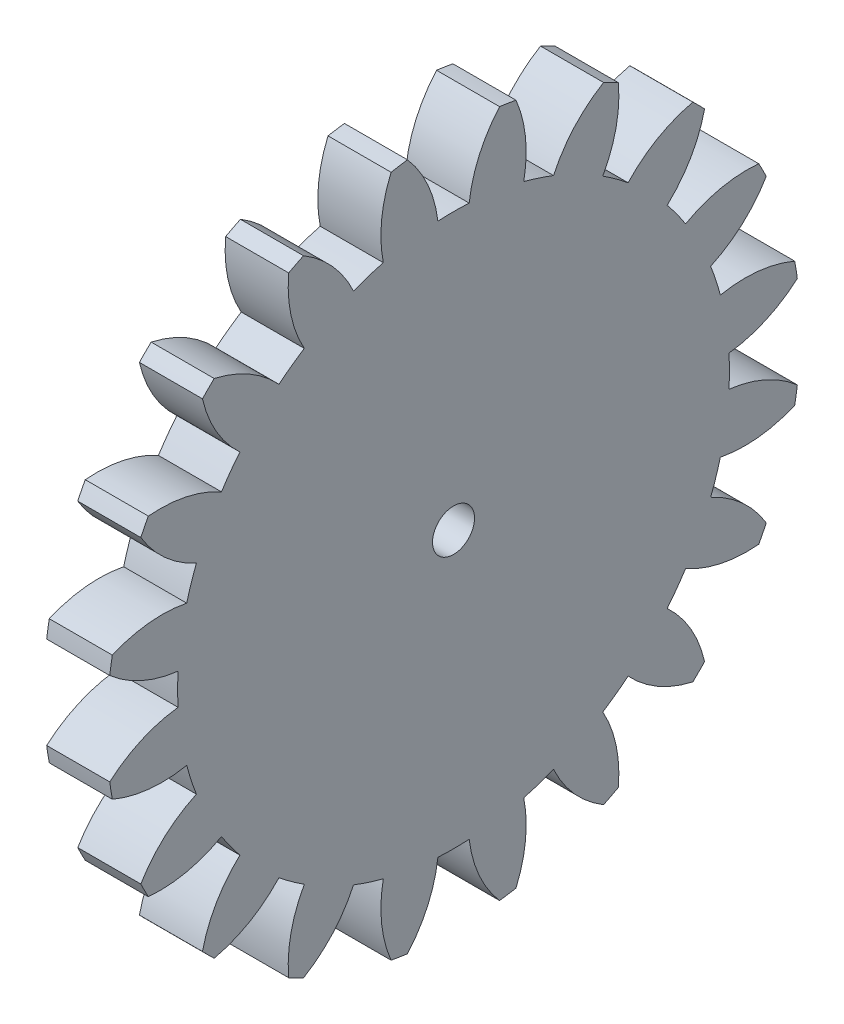
SolidWorks part; units mm, degrees
ref_plane "Plane1" through (0, 0, 0) normal (0, 0, 1) x (1, 0, 0)
ref_plane "Plane2" through (0, 0, 0) normal (0, 1, 0) x (1, 0, 0)
ref_plane "Plane3" through (0, 0, 0) normal (1, 0, 0) x (0, 0, -1)
other "Configuration Table"
sketch "HoldingSke" plane through (0, 0, 0) normal (0, 1, 0) x (1, 0, 0)
  line L0 (0, 0) -> (0.3132, -0.114)
  line L1 (-15, 0) -> (100, 0) construction
  line L2 (0, 0) -> (-2.1039, 2.3779)
  line L3 (0, 0) -> (-11.863, 4.5341)
  line L4 (0, 0) -> (8.1152, 2.9537)
  line L5 (0, 0) -> (-46.8476, -17.4728)
  line L6 (0, 0) -> (-4.9738, -3.3558)
  line L7 (-2.1039, 2.3779) -> (8.6586, 51.2059)
  line L8 (-76.2, 54.61) -> (-75.5, 54.61)
  line L9 (-71.009, 38.7566) -> (-53.1078, 45.2721)
  line L10 (-76.2, 71.12) -> (104.1128, 71.12)
  line L11 (0, 0) -> (-6, 0)
  line L12 (-76.2, 101.6) -> (-76.093, 101.6)
  line L13 (24.9733, 27.94) -> (52.9518, 28.4284)
  line L14 (24.9733, 27.94) -> (24.9743, 27.94)
  line L15 (24.9733, 27.94) -> (100.4006, 29.5858)
  line L16 (-63.627, -3) -> (-12.827, -3)
  circle A0 centre (0, 0) radius 2
  circle A1 centre (0, 0) radius 26.249
  circle A2 centre (0, 0) radius 37.5
  circle A3 centre (0, 0) radius 2
  dimension "MHD" = 52.498
  dimension "Hub_dia" = 75
  dimension "Bore" = 4
  dimension "MBD" = 4
  dimension "Num_teeth" = 20
  dimension "Pitch" = 0.3333
  dimension "Overall_len" = 50
  dimension "Show_teeth" = 20
  dimension "Thickness" = 6
  dimension "OAL" = 50.0001
  dimension "T_dim" = 0.7
  dimension "Ap" = 20
  dimension "H" = 19.05
  dimension "Pitch_radius" = 180.3128
  dimension "Width" = 6
  dimension "Backlash" = 0.107
  dimension "Addendum_fac" = 1
  dimension "Dedendum_fac" = 1.25
  dimension "Clearance_fac" = 0.25
  dimension "Dedendum_add" = 0.001
  dimension "Module" = 3
sketch "BasProSke" plane through (0, 0, 0) normal (0, 1, 0) x (1, 0, 0)
  line L0 (-10, 0) -> (60, 0) construction
  line L1 (0, 0) -> (0, 33)
  line L2 (0, 0) -> (6, 0)
  line L3 (6, 0) -> (6, 33)
  line L4 (6, 33) -> (0, 33)
  dimension "Thickness" = 6
  dimension "Diameter" = 66
revolve "Base-Revolve" add sketch "BasProSke" angle 360 about L0
sketch "TooCutSke" plane through (0, 0, 0) normal (1, 0, 0) x (0, 0, -1)
  line L1 (0, 0) -> (0, 107) construction
  line L2 (0, 0) -> (-2.5409, 29.8922) construction
  line L3 (0, 0) -> (-9.3616, 59.1066) construction
  line L4 (-2.5409, 29.8922) -> (-4.6808, 29.5533) construction
  arc A0 (1.4893, 26.2067) -> (-1.4893, 26.2067) centre (0, 0) ccw
  arc A1 (4.4016, 32.7308) -> (-4.4016, 32.7308) centre (0, 0) ccw
  circle A2 centre (0, 0) radius 30 construction
  circle A3 centre (0, 0) radius 28.1908 construction
  arc A4 (-1.4893, 26.2067) -> (-4.4016, 32.7308) centre (-13.4064, 24.799) ccw
  arc A5 (4.4016, 32.7308) -> (1.4893, 26.2067) centre (13.4064, 24.799) ccw
  dimension "Root_dia" = 52.498
  dimension "Overcut_dia" = 66.0508
  dimension "Pitch_dia" = 60
  dimension "Base_dia" = 56.3816
  dimension "Flank_rad" = 12
  dimension "Half_ang" = 9
  dimension "Half_CT" = 2.1665
extrude "ToothCut" cut sketch "TooCutSke" along normal through all
fillet "Breaks" [suppressed] radius 0.06
fillet "RootFillets" [suppressed] radius 0.751
pattern_circular "TeethCuts" count 20 every 18 about axis through (-10, 0, 0) along (1, 0, 0) of "ToothCut", "RootFillets", "Breaks"
sketch "HubNeaOneSke" plane through (0, 0, 0) normal (-1, 0, 0) x (0, 0, 1)
  circle A0 centre (0, 0) radius 26.249
  dimension "Diameter" = 52.498
extrude "HubNearOne" [suppressed] add sketch "HubNeaOneSke" along normal blind 44.0001
sketch "HubNeaBotSke" plane through (0, 0, 0) normal (-1, 0, 0) x (0, 0, 1)
  circle A0 centre (0, 0) radius 26.249
  dimension "Diameter" = 52.498
extrude "HubNearBoth" [suppressed] add sketch "HubNeaBotSke" along normal blind 22
ref_plane "FarPln" through (6, 0, 0) normal (1, 0, 0) x (0, 0, -1)
sketch "HubFarSke" plane through (6, 0, 0) normal (1, 0, 0) x (0, 0, -1)
  circle A0 centre (0, 0) radius 26.249
  dimension "Diameter" = 52.498
extrude "HubFar" [suppressed] add sketch "HubFarSke" along normal blind 22
sketch "BorSke" plane through (0, 0, 0) normal (1, 0, 0) x (0, 0, -1)
  circle A0 centre (0, 0) radius 2
  dimension "Diameter" = 4
extrude "Bore" cut sketch "BorSke" along normal mid plane 100.0001
sketch "KeySke" plane through (0, 0, 0) normal (1, 0, 0) x (0, 0, -1)
  line L0 (-0.8, 0) -> (-0.8, 2.7)
  line L1 (-0.8, 2.7) -> (0.8, 2.7)
  line L2 (0.8, 2.7) -> (0.8, 0)
  line L3 (0, 0) -> (0, 34) construction
  line L4 (-0.8, 0) -> (0.8, 0)
  dimension "Offset" = 2.7
  dimension "Width" = 1.6
extrude "Keyway" [suppressed] cut sketch "KeySke" along normal mid plane 100.0001
pattern_circular "Keyway2" [suppressed] count 2 every 90 about axis through (-10, 0, 0) along (1, 0, 0)
equation "' \"Module@HoldingSke\" = 6.35"
equation "' \"Num_teeth@HoldingSke\" = 12"
equation "' \"Ap@HoldingSke\" =  20"
equation "' \"Ap@HoldingSke\" = 20"
equation "' \"Width@HoldingSke\" = 0.5 * 25.4"
equation "' \"Hub_dia@HoldingSke\"= 1 * 25.4"
equation "' \"Hub_dia@HoldingSke\" = 1 * 25.4"
equation "' \"Overall_len@HoldingSke\" = 1.0 * 25.4"
equation "' \"Bore@HoldingSke\" = 0.75 * 25.4"
equation "' \"T_dim@HoldingSke\" = 0.1 * 25.4"
equation "' \"Width@KeySke\" = 0.25 * 25.4"
equation "' \"Show_teeth@HoldingSke\" = 13"
equation "' \"Backlash@HoldingSke\" = 0.009 * 25.4"
equation "' \"Addendum_fac@HoldingSke\" = 1.0"
equation "' \"Dedendum_fac@HoldingSke\" = 1.25"
equation "' \"Dedendum_add@HoldingSke\" = 0.00005 * 25.4"
equation "' \"Clearance_fac@HoldingSke\" = 0.25"
equation "\"Pitch@HoldingSke\" = 1 / \"Module@HoldingSke\""
equation "\"Overcut_dia@TooCutSke\" = (\"Num_teeth@HoldingSke\" + 2 * \"Addendum_fac@HoldingSke\") / \"Pitch@HoldingSke\" + 0.002 * 25.4"
equation "\"Pitch_dia@TooCutSke\" = \"Num_teeth@HoldingSke\" / \"Pitch@HoldingSke\""
equation "\"Base_dia@TooCutSke\" = \"Num_teeth@HoldingSke\" / \"Pitch@HoldingSke\" * cos((\"Ap@HoldingSke\"  * 3.14159265 / 180))"
equation "\"Root_dia@TooCutSke\" = (\"Num_teeth@HoldingSke\" + 2) / \"Pitch@HoldingSke\" - 2 * (\"Addendum_fac@HoldingSke\" + \"Dedendum_fac@HoldingSke\") / \"Pitch@HoldingSke\" - \"Dedendum_add@HoldingSke\" * 2"
equation "\"Half_ang@TooCutSke\" = 180 / \"Num_teeth@HoldingSke\""
equation "\"Half_CT@TooCutSke\" = \"Num_teeth@HoldingSke\" / \"Pitch@HoldingSke\" * sin((3.14159265 / 2 / \"Num_teeth@HoldingSke\")) / 2 - 7 * \"Backlash@HoldingSke\" / 4"
equation "\"Flank_rad@TooCutSke\" = \"Num_teeth@HoldingSke\" / \"Pitch@HoldingSke\" / 5"
equation "\"Radius@RootFillets\" = \"Clearance_fac@HoldingSke\" / \"Pitch@HoldingSke\" + \"Dedendum_add@HoldingSke\""
equation "\"Break_rad@Breaks\" = 0.02 / \"Pitch@HoldingSke\""
equation "\"Thickness@HoldingSke\" = \"Width@HoldingSke\""
equation "\"OAL@HoldingSke\" = \"Thickness@HoldingSke\""
equation "\"MHD@HoldingSke\" = (\"Num_teeth@HoldingSke\" + 2) / \"Pitch@HoldingSke\" - 2 * (\"Addendum_fac@HoldingSke\" + \"Dedendum_fac@HoldingSke\")  / \"Pitch@HoldingSke\" - \"Dedendum_add@HoldingSke\" * 2"
equation "\"MBD@HoldingSke\" = (\"Num_teeth@HoldingSke\" + 2) / \"Pitch@HoldingSke\" - 2 * (\"Addendum_fac@HoldingSke\" + \"Dedendum_fac@HoldingSke\")  / \"Pitch@HoldingSke\" - \"Dedendum_add@HoldingSke\" * 2 - 0.002 * 25.4"
equation "\"MHD@HoldingSke\" = ((sgn( \"MHD@HoldingSke\" - \"Hub_dia@HoldingSke\" )-1)*( \"MHD@HoldingSke\" - \"Hub_dia@HoldingSke\" ))/-2+ \"Hub_dia@HoldingSke\""
equation "\"MBD@HoldingSke\" = ((sgn( \"MBD@HoldingSke\" - \"Bore@HoldingSke\" )-1)*( \"MBD@HoldingSke\" - \"Bore@HoldingSke\" ))/-2+ \"Bore@HoldingSke\""
equation "\"OAL@HoldingSke\" = ((sgn( \"OAL@HoldingSke\" - \"Overall_len@HoldingSke\" )+1)*( \"OAL@HoldingSke\" - \"Overall_len@HoldingSke\" ))/2 + \"Overall_len@HoldingSke\" + 0.000002 * 25.4"
equation "\"Num_teeth@TeethCuts\" = int( \"Show_teeth@HoldingSke\" ) + 1"
equation "\"Num_teeth@TeethCuts\" = ((sgn( \"Num_teeth@TeethCuts\" - \"Num_teeth@HoldingSke\" )-1)*( \"Num_teeth@TeethCuts\" - \"Num_teeth@HoldingSke\" ))/-2+ \"Num_teeth@HoldingSke\""
equation "\"Num_teeth@TeethCuts\" = ((sgn( \"Num_teeth@TeethCuts\" - 2.0)+1)*( \"Num_teeth@TeethCuts\" - 2.0))/2 +2.0"
equation "\"Angle@TeethCuts\" = 360.0 / \"Num_teeth@HoldingSke\""
equation "\"Diameter@BasProSke\" = (\"Num_teeth@HoldingSke\" + 2 * \"Addendum_fac@HoldingSke\") / \"Pitch@HoldingSke\""
equation "\"Thickness@BasProSke\"  = \"Thickness@HoldingSke\""
equation "' \"Fillet_rad@BasProSke\" =  \"Thickness@HoldingSke\" * 0.05"
equation "' \"Fillet_rad@BasProSke\" = \"Thickness@HoldingSke\" * 0.05"
equation "\"MHD@HoldingSke\" = ((sgn( \"MHD@HoldingSke\" - \"Root_dia@TooCutSke\" )-1)*( \"MHD@HoldingSke\" - \"Root_dia@TooCutSke\" ))/-2+ \"Root_dia@TooCutSke\""
equation "\"Diameter@HubNeaOneSke\" = \"MHD@HoldingSke\""
equation "\"Length@HubNearOne\" = \"OAL@HoldingSke\" - \"Thickness@BasProSke\""
equation "\"Diameter@HubNeaBotSke\" = \"MHD@HoldingSke\""
equation "\"Length@HubNearBoth\" = ( \"OAL@HoldingSke\" - \"Thickness@BasProSke\" ) / 2.0"
equation "\"Thickness@FarPln\" = \"Thickness@BasProSke\""
equation "\"Diameter@HubFarSke\" = \"MHD@HoldingSke\""
equation "\"Length@HubFar\" = ( \"OAL@HoldingSke\" - \"Thickness@BasProSke\" ) / 2.0"
equation "\"Diameter@BorSke\" = \"MBD@HoldingSke\""
equation "\"D1@Bore\" = \"OAL@HoldingSke\" * 2.0"
equation "\"D1@Keyway\" = \"OAL@HoldingSke\" * 2.0"
equation "\"Offset@KeySke\" = \"T_dim@HoldingSke\" + \"MBD@HoldingSke\" / 2.0"
